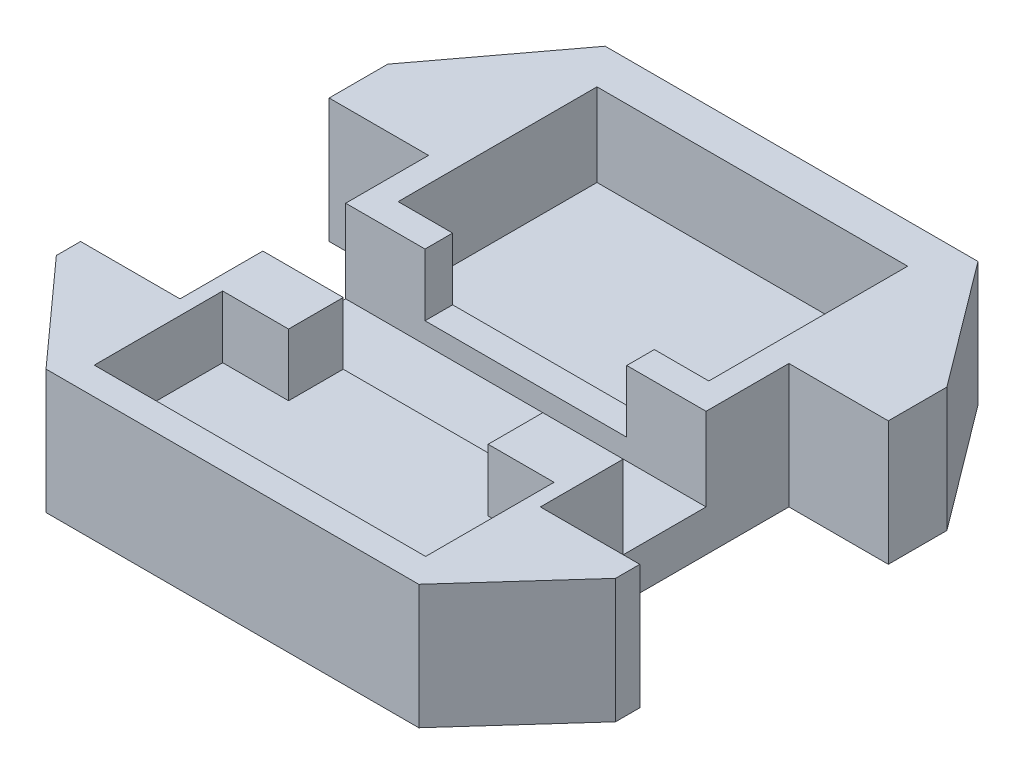
SolidWorks part; units mm, degrees
material "Homopolímero PP"
ref_plane "Plano frontal" through (0, 0, 0) normal (0, 0, 1) x (1, 0, 0)
ref_plane "Plano superior" through (0, 0, 0) normal (0, 1, 0) x (1, 0, 0)
ref_plane "Plano direito" through (0, 0, 0) normal (1, 0, 0) x (0, 0, -1)
sketch "Esboço2" plane through (0, 0, 0) normal (0, 1, 0) x (1, 0, 0)
  line L0 (-1000, 22.5) -> (49000, 22.5) construction
  line L1 (0, -1000) -> (0, 49000) construction
  line L2 (-45, -45) -> (45, -45)
  line L3 (45, -45) -> (67.5, -20)
  line L4 (67.5, -20) -> (67.5, 60)
  line L5 (67.5, 60) -> (45, 90)
  line L6 (45, 90) -> (-45, 90)
  line L7 (1000, 22.5) -> (-49000, 22.5) construction
  line L8 (-67.5, 60) -> (-45, 90)
  line L9 (-67.5, -20) -> (-67.5, 60)
  line L10 (-45, -45) -> (-67.5, -20)
  circle A0 centre (0, 90) radius 50 construction
  point P18 (0, -45)
  dimension "D7" = 100
  dimension "D1" = 45
  dimension "D2" = 25
  dimension "D3" = 80
  dimension "D4" = 30
  dimension "D5" = 45
  dimension "D6" = 135
extrude "Ressalto-extrusão1" add sketch "Esboço2" along normal blind 30
sketch "Esboço3" plane through (0, 30, 0) normal (0, 1, 0) x (1, 0, 0)
  line L0 (-67.5, 60) -> (-67.5, -20) construction
  line L1 (-67.5, 45.8497) -> (-43.5, 45.8497)
  line L2 (-67.5, 45.8497) -> (-67.5, -14.1503)
  line L3 (-67.5, -14.1503) -> (-43.5, -14.1503)
  line L4 (-43.5, 45.8497) -> (-43.5, -14.1503)
  line L5 (67.5, -20) -> (67.5, 60) construction
  line L6 (43.5, 45.8497) -> (67.5, 45.8497)
  line L7 (43.5, 45.8497) -> (43.5, -14.1503)
  line L8 (43.5, -14.1503) -> (67.5, -14.1503)
  line L9 (67.5, 45.8497) -> (67.5, -14.1503)
  line L10 (45, 90) -> (-45, 90) construction
  dimension "D1" = 60
  dimension "D2" = 60
  dimension "D3" = 24
  dimension "D4" = 24
  dimension "D5" = 44.1503
extrude "Corte-extrusão1" cut sketch "Esboço3" against normal through all both and the other way through all
sketch "Esboço4" plane through (0, 30, 0) normal (0, 1, 0) x (1, 0, 0)
  line L0 (-67.5, -14.1503) -> (-43.5, -14.1503) construction
  line L1 (-64.0732, 25.8497) -> (58.1544, 25.8497)
  line L2 (-64.0732, 25.8497) -> (-64.0732, 5.8497)
  line L3 (-64.0732, 5.8497) -> (58.1544, 5.8497)
  line L4 (58.1544, 25.8497) -> (58.1544, 5.8497)
  line L5 (-64.0732, 25.8497) -> (58.1544, 5.8497) construction
  line L6 (-64.0732, 5.8497) -> (58.1544, 25.8497) construction
  point P0 (-2.9594, 15.8497)
  dimension "D1" = 20
  dimension "D2" = 20
extrude "Corte-extrusão3" cut sketch "Esboço4" against normal blind 20
sketch "Esboço6" plane through (0, 30, 0) normal (0, 1, 0) x (1, 0, 0)
  line L1 (-40, -7.3508) -> (40, -7.3508)
  line L2 (-40, -7.3508) -> (-40, -38.3508)
  line L3 (-40, -38.3508) -> (40, -38.3508)
  line L4 (40, -7.3508) -> (40, -38.3508)
  line L7 (43.5, 5.8497) -> (43.5, -14.1503) construction
  line L9 (-45, -45) -> (45, -45) construction
  point P4 (40.0999, -38.3508)
  dimension "D1" = 80
  dimension "D2" = 31
  dimension "D3" = 3.5
  dimension "D4" = 6.6492
extrude "Corte-extrusão5" cut sketch "Esboço6" against normal blind 15
sketch "Esboço8" plane through (0, 30, 0) normal (0, 1, 0) x (1, 0, 0)
  line L0 (-43.5, 5.8497) -> (43.5, 5.8497) construction
  line L1 (-24.09, 5.8497) -> (24.09, 5.8497)
  line L2 (-24.09, 5.8497) -> (-24.09, -7.3508)
  line L3 (-24.09, -7.3508) -> (24.09, -7.3508)
  line L4 (24.09, 5.8497) -> (24.09, -7.3508)
  line L5 (40, -7.3508) -> (-40, -7.3508) construction
  line L7 (43.5, 5.8497) -> (43.5, -14.1503) construction
  line L8 (-43.5, -14.1503) -> (-43.5, 5.8497) construction
  point P4 (0, 0)
  point P5 (-24.3698, 5.8497)
  point P8 (23.8121, -11.0467)
  point P9 (23.8121, -7.3508)
  dimension "D1" = 19.41
  dimension "D2" = 19.41
extrude "Corte-extrusão6" cut sketch "Esboço8" against normal blind 15
sketch "Esboço9" plane through (0, 30, 0) normal (0, 1, 0) x (1, 0, 0)
  line L1 (-37.5, 80.5159) -> (37.5, 80.5159)
  line L2 (-37.5, 80.5159) -> (-37.5, 32.5159)
  line L3 (-37.5, 32.5159) -> (37.5, 32.5159)
  line L4 (37.5, 80.5159) -> (37.5, 32.5159)
  line L5 (43.5, 45.8497) -> (43.5, 25.8497) construction
  dimension "D1" = 48
  dimension "D2" = 75
  dimension "D3" = 6
extrude "Corte-extrusão7" cut sketch "Esboço9" against normal blind 20
sketch "Esboço10" plane through (0, 30, 0) normal (0, 1, 0) x (1, 0, 0)
  line L0 (-37.5, 32.5159) -> (37.5, 32.5159) construction
  line L1 (-24.35, 32.5159) -> (24.35, 32.5159)
  line L2 (-24.35, 32.5159) -> (-24.35, 25.8497)
  line L3 (-24.35, 25.8497) -> (24.35, 25.8497)
  line L4 (24.35, 32.5159) -> (24.35, 25.8497)
  line L5 (43.5, 25.8497) -> (-43.5, 25.8497) construction
  point P8 (0, 0)
  point P16 (0, 0)
  point P18 (0, 0)
  point P20 (0, 0)
  point P22 (0, 0)
  dimension "D1" = 19.15
  dimension "D2" = 19.15
extrude "Corte-extrusão8" cut sketch "Esboço10" against normal blind 15
